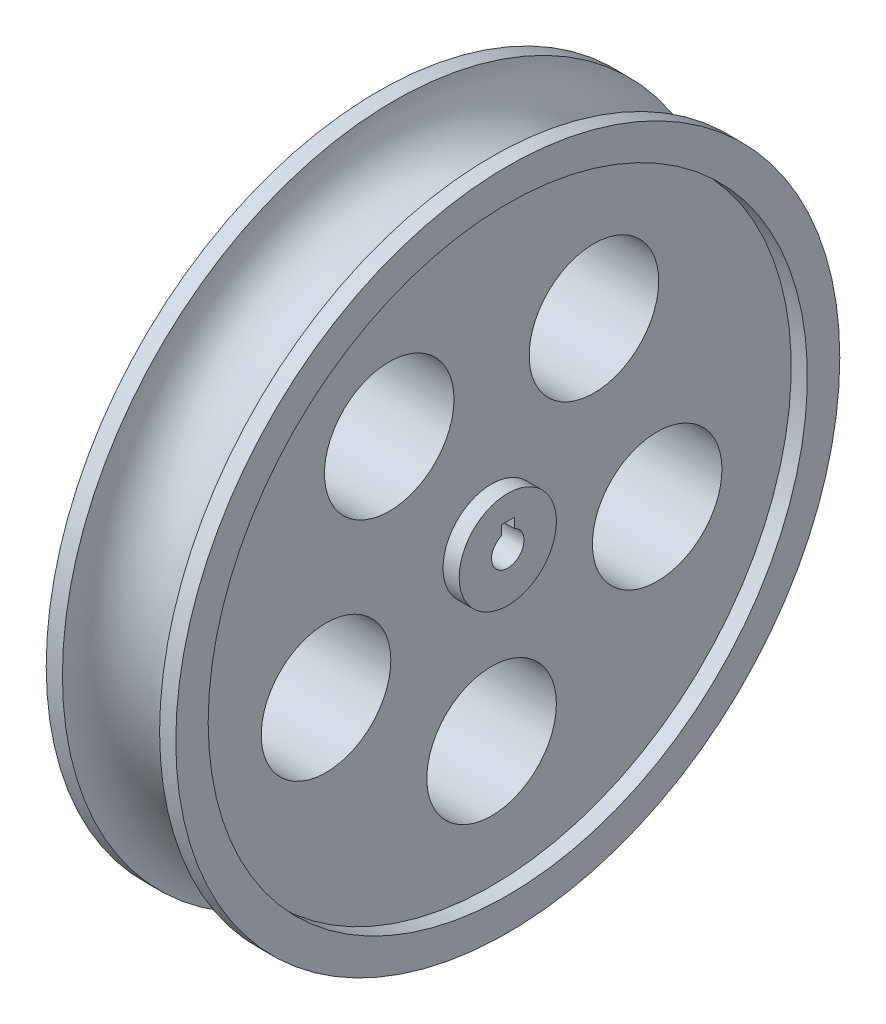
SolidWorks part; units mm, degrees
ref_plane "Front Plane" through (0, 0, 0) normal (0, 0, 1) x (1, 0, 0)
ref_plane "Top Plane" through (0, 0, 0) normal (0, 1, 0) x (1, 0, 0)
ref_plane "Right Plane" through (0, 0, 0) normal (1, 0, 0) x (0, 0, -1)
sketch "Sketch1" plane through (0, 0, 0) normal (0, 0, 1) x (1, 0, 0)
  line L0 (0, 43.1257) -> (0, -52.2833) construction
  line L1 (-60.7608, 0) -> (61.5381, 0) construction
  line L2 (-75, 25) -> (75, 25)
  line L3 (75, 25) -> (100, 25)
  line L4 (100, 25) -> (100, 75)
  line L5 (100, 75) -> (75, 75)
  line L6 (75, 75) -> (75, 462.5)
  line L7 (75, 462.5) -> (100, 462.5)
  line L8 (100, 462.5) -> (100, 512.5)
  line L9 (100, 512.5) -> (75, 512.5)
  line L10 (-75, 512.5) -> (-100, 512.5)
  line L11 (-100, 512.5) -> (-100, 462.5)
  line L12 (-100, 462.5) -> (-75, 462.5)
  line L13 (-75, 462.5) -> (-75, 75)
  line L14 (-75, 75) -> (-100, 75)
  line L15 (-100, 75) -> (-100, 25)
  line L16 (-100, 25) -> (-75, 25)
  arc A0 (75, 512.5) -> (-75, 512.5) centre (0, 512.5) cw
  point P8 (0, 25)
  dimension "D2" = 25
  dimension "D8" = 75
  dimension "D1" = 25
  dimension "D3" = 50
  dimension "D4" = 387.5
  dimension "D5" = 25
  dimension "D6" = 50
  dimension "D7" = 25
  dimension "D9" = 25
  dimension "D10" = 50
  dimension "D11" = 25
  dimension "D12" = 387.5
  dimension "D13" = 25
revolve "Revolve2" add sketch "Sketch1" angle 360 about L1
sketch "Sketch2" plane through (100, 0, 0) normal (1, 0, 0) x (0, 0, -1)
  line L0 (-10, 37.9129) -> (10, 37.9129)
  line L1 (-10, 37.9129) -> (-10, 22.9129)
  line L2 (-10, 22.9129) -> (10, 22.9129)
  line L3 (10, 22.9129) -> (10, 37.9129)
  circle A0 centre (0, 0) radius 25 construction
  point P3 (0, 37.9129)
  dimension "D1" = 20
  dimension "D2" = 15
extrude "Cut-Extrude1" cut sketch "Sketch2" against normal blind 200
sketch "Sketch3" plane through (75, 0, 0) normal (1, 0, 0) x (0, 0, -1)
  circle A0 centre (0, -268.75) radius 100
  circle A1 centre (-255.5964, -83.0483) radius 100
  circle A2 centre (-157.9673, 217.4233) radius 100
  circle A3 centre (157.9673, 217.4233) radius 100
  circle A4 centre (255.5964, -83.0483) radius 100
  point P13 (0, 0)
  dimension "D1" = 200
  dimension "D2" = 268.75
  dimension "D3" = 5
extrude "Cut-Extrude2" cut sketch "Sketch3" against normal blind 200
